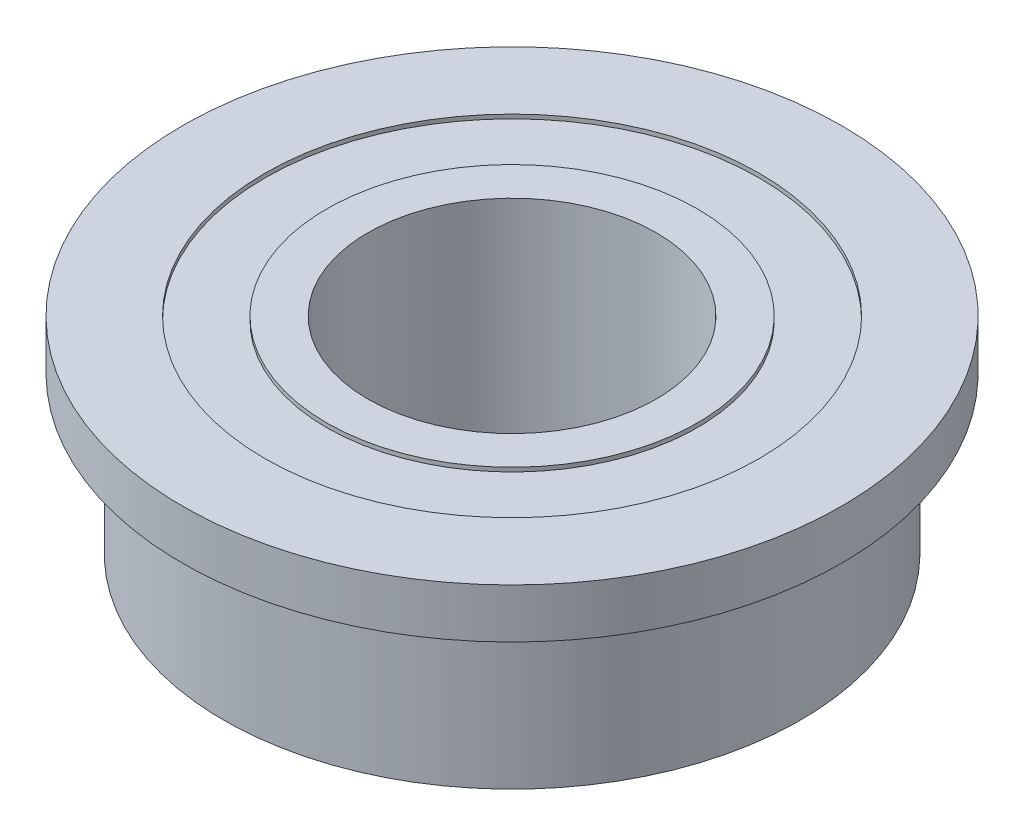
SolidWorks part; units mm, degrees
ref_plane "前视基准面" through (0, 0, 0) normal (0, 0, 1) x (1, 0, 0)
ref_plane "上视基准面" through (0, 0, 0) normal (0, 1, 0) x (1, 0, 0)
ref_plane "右视基准面" through (0, 0, 0) normal (1, 0, 0) x (0, 0, -1)
other "Configuration Table"
sketch "草图1" plane through (0, 0, 0) normal (0, 0, 1) x (1, 0, 0)
  line L0 (3.5, 0) -> (3.5, 5)
  line L1 (3.5, 5) -> (8, 5)
  line L2 (8, 5) -> (8, 3.8)
  line L3 (8, 3.8) -> (7, 3.8)
  line L4 (7, 3.8) -> (7, 0)
  line L5 (7, 0) -> (3.5, 0)
  line L6 (0, 0) -> (3.5, 0) construction
  line L7 (0, 0) -> (0, 5.7172) construction
  dimension "D1" = 5
  dimension "D2" = 8
  dimension "D3" = 1.2
  dimension "D4" = 7
  dimension "D5" = 3.5
  dimension "D6" = 5.7172
revolve "旋转1" add sketch "草图1" angle 360 about L7
sketch "草图2" plane through (0, 0, 0) normal (0, -1, 0) x (1, 0, 0)
  circle A0 centre (0, 0) radius 6
  circle A1 centre (0, 0) radius 4.5
  dimension "D1" = 12
  dimension "D2" = 9
extrude "切除-拉伸1" cut sketch "草图2" against normal mid plane 0.2
sketch "草图3" plane through (0, 5, 0) normal (0, 1, 0) x (1, 0, 0)
  circle A0 centre (0, 0) radius 4.5
  circle A1 centre (0, 0) radius 6
  dimension "D1" = 9
  dimension "D2" = 12
extrude "切除-拉伸2" cut sketch "草图3" against normal mid plane 0.2
